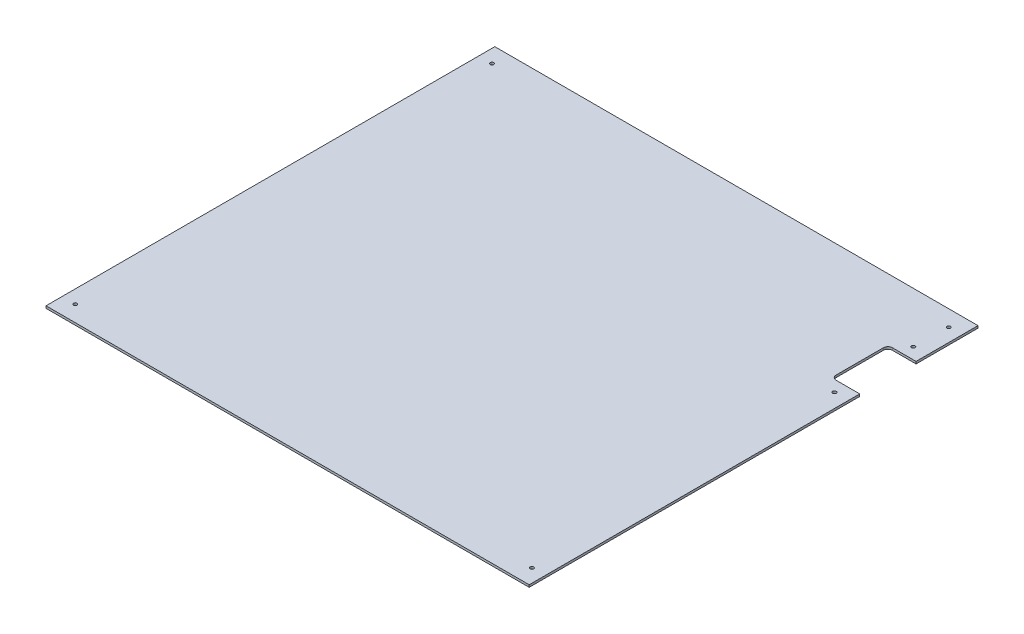
SolidWorks part; units mm, degrees
ref_plane "Alzado" through (0, 0, 0) normal (0, 0, 1) x (1, 0, 0)
ref_plane "Planta" through (0, 0, 0) normal (0, 1, 0) x (1, 0, 0)
ref_plane "Vista lateral" through (0, 0, 0) normal (1, 0, 0) x (0, 0, -1)
sketch "Croquis1" plane through (0, 0, 0) normal (0, 1, 0) x (1, 0, 0)
  line L1 (0, 0) -> (430.5, 0)
  line L2 (0, 0) -> (0, 400)
  line L3 (0, 400) -> (430.5, 400)
  line L4 (430.5, 0) -> (430.5, 400)
  dimension "D1" = 400
  dimension "D2" = 430.5
extrude "Saliente-Extruir1" add sketch "Croquis1" along normal blind 2
sketch "Croquis2" plane through (0, 2, 0) normal (0, 1, 0) x (1, 0, 0)
  line L0 (430.5, 400) -> (0, 400) construction
  line L1 (0, 400) -> (0, 0) construction
  line L2 (215.25, 400) -> (215.25, 0) construction
  line L3 (0, 0) -> (430.5, 0) construction
  line L4 (0, 200) -> (430.5, 200) construction
  line L5 (430.5, 0) -> (430.5, 400) construction
  circle A0 centre (12.5, 385) radius 1.55
  circle A1 centre (418, 385) radius 1.55
  circle A2 centre (418, 15) radius 1.55
  circle A3 centre (12.5, 15) radius 1.55
  dimension "D1" = 3.1
  dimension "D2" = 15
  dimension "D3" = 12.5
extrude "Cortar-Extruir1" cut sketch "Croquis2" against normal up to surface (2 mm away) up to face at (215.25, 0, -200)
sketch "Croquis3" plane through (0, 2, 0) normal (0, 1, 0) x (1, 0, 0)
  line L0 (429.75, 399.25) -> (0.75, 399.25)
  line L1 (0.75, 399.25) -> (0.75, 0.75)
  line L2 (0.75, 0.75) -> (429.75, 0.75)
  line L3 (429.75, 0.75) -> (429.75, 399.25)
  line L4 (0, 400) -> (0, 0)
  line L5 (0, 0) -> (430.5, 0)
  line L6 (430.5, 0) -> (430.5, 400)
  line L7 (430.5, 400) -> (0, 400)
  line L8 (0, 400) -> (0, 0)
  line L9 (0, 0) -> (430.5, 0)
  line L10 (430.5, 0) -> (430.5, 400)
  line L11 (430.5, 400) -> (0, 400)
  dimension "D1" = 0
  dimension "D2" = 0.75
extrude "Cortar-Extruir2" cut sketch "Croquis3" against normal up to surface (2 mm away) up to face at (12.5, 0, -16.55)
sketch "Croquis4" plane through (0, 2, 0) normal (0, 1, 0) x (1, 0, 0)
  line L0 (429.75, 0.75) -> (429.75, 399.25) construction
  line L1 (429.75, 344.25) -> (404.75, 344.25)
  line L2 (429.75, 344.25) -> (429.75, 294.25)
  line L3 (429.75, 294.25) -> (404.75, 294.25)
  line L4 (404.75, 344.25) -> (404.75, 294.25)
  line L5 (429.75, 399.25) -> (0.75, 399.25) construction
  dimension "D1" = 25
  dimension "D2" = 50
  dimension "D3" = 55
extrude "Cortar-Extruir3" cut sketch "Croquis4" against normal up to surface (2 mm away) up to face at (12.5, 0, -386.55)
fillet "Redondeo1" radius 4 2 edges at (404.75, 1, -294.25) (404.75, 1, -344.25)
sketch "Croquis5" plane through (0, 2, 0) normal (0, 1, 0) x (1, 0, 0)
  line L0 (429.75, 344.25) -> (408.75, 344.25) construction
  line L1 (408.75, 294.25) -> (429.75, 294.25) construction
  line L2 (429.75, 344.25) -> (429.75, 399.25) construction
  line L3 (429.75, 0.75) -> (429.75, 294.25) construction
  circle A0 centre (417.25, 354.25) radius 1.6
  circle A1 centre (417.25, 284.25) radius 1.6
  dimension "D4" = 3.2
  dimension "D1" = 10
  dimension "D2" = 12.5
  dimension "10" = 10
  dimension "D3" = 12.5
extrude "Cortar-Extruir4" cut sketch "Croquis5" against normal up to surface (2 mm away) up to face at (334.5843, 0, -271.55)
